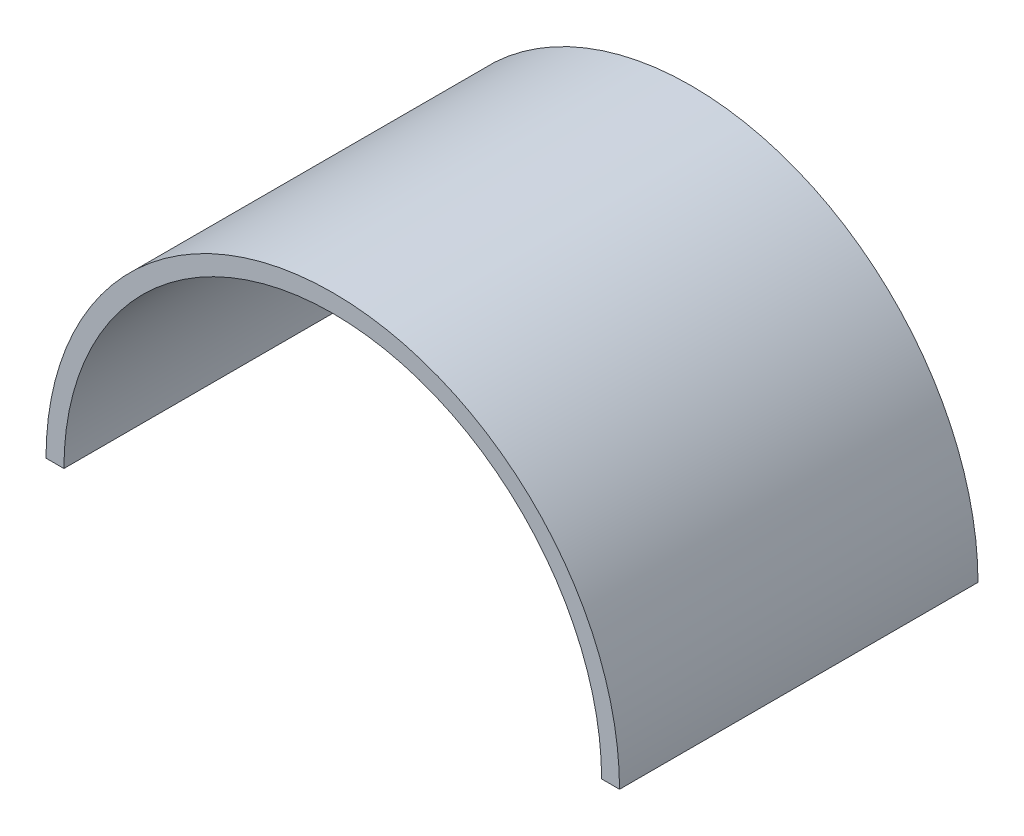
SolidWorks part; units mm, degrees
ref_plane "Front Plane" through (0, 0, 0) normal (0, 0, 1) x (1, 0, 0)
ref_plane "Top Plane" through (0, 0, 0) normal (0, 1, 0) x (1, 0, 0)
ref_plane "Right Plane" through (0, 0, 0) normal (1, 0, 0) x (0, 0, -1)
sketch "Sketch1" plane through (0, 0, 0) normal (0, 0, 1) x (1, 0, 0)
  line L0 (47.625, 0) -> (50.8, 0)
  line L1 (-47.625, 0) -> (-50.8, 0)
  arc A0 (50.8, 0) -> (-50.8, 0) centre (0, 0) ccw
  arc A1 (47.625, 0) -> (-47.625, 0) centre (0, 0) ccw
  dimension "D1" = 101.6
  dimension "D2" = 95.25
extrude "Boss-Extrude2" add sketch "Sketch1" along normal blind 63.5
